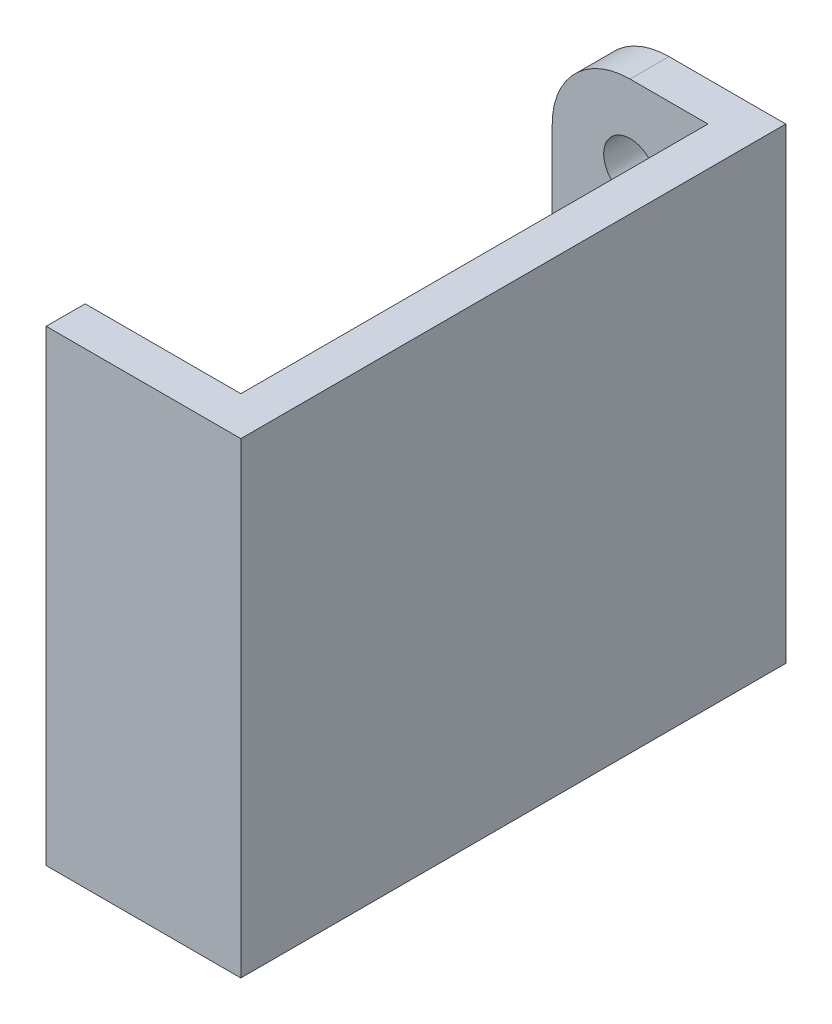
SolidWorks part; units mm, degrees
material "PET"
ref_plane "Front Plane" through (0, 0, 0) normal (0, 0, 1) x (1, 0, 0)
ref_plane "Top Plane" through (0, 0, 0) normal (0, 1, 0) x (1, 0, 0)
ref_plane "Right Plane" through (0, 0, 0) normal (1, 0, 0) x (0, 0, -1)
sketch "Sketch1" plane through (0, 0, 0) normal (0, 0, 1) x (1, 0, 0)
  line L1 (-7.9375, 19.05) -> (7.9375, 19.05)
  line L2 (-7.9375, 19.05) -> (-7.9375, -19.05)
  line L3 (-7.9375, -19.05) -> (7.9375, -19.05)
  line L4 (7.9375, 19.05) -> (7.9375, -19.05)
  line L5 (-7.9375, 19.05) -> (7.9375, -19.05) construction
  line L6 (-7.9375, -19.05) -> (7.9375, 19.05) construction
  point P0 (0, 0)
  dimension "D1" = 38.1
  dimension "D2" = 15.875
extrude "Boss-Extrude1" add sketch "Sketch1" against normal blind 44.45
shell "Shell1" thickness 3.175
sketch "Sketch2" plane through (0, 0, -3.175) normal (0, 0, 1) x (1, 0, 0)
  line L0 (7.9375, 19.05) -> (-7.9375, 19.05) construction
  line L1 (-7.9375, 19.05) -> (-7.9375, -19.05) construction
  circle A0 centre (-1.5875, -6.35) radius 2.1526
  circle A1 centre (-1.5875, 12.7) radius 2.1526
  dimension "D1" = 4.3053
  dimension "D2" = 19.05
  dimension "D3" = 6.35
  dimension "D4" = 6.35
extrude "Cut-Extrude1" cut sketch "Sketch2" against normal up to next
fillet "Fillet2" radius 6.35 1 edges at (-7.9375, 19.05, -42.8625)
